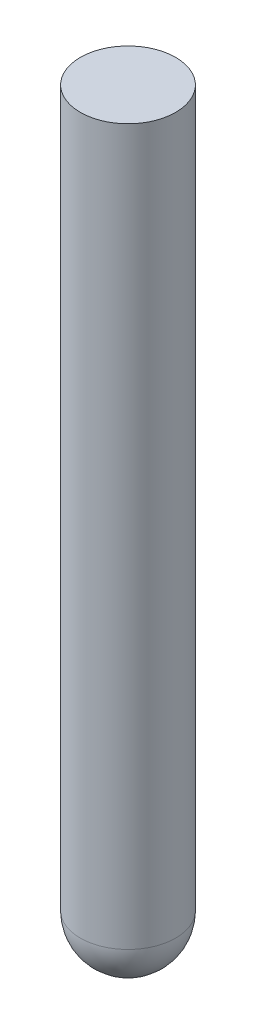
SolidWorks part; units mm, degrees
ref_plane "Front Plane" through (0, 0, 0) normal (0, 0, 1) x (1, 0, 0)
ref_plane "Top Plane" through (0, 0, 0) normal (0, 1, 0) x (1, 0, 0)
ref_plane "Right Plane" through (0, 0, 0) normal (1, 0, 0) x (0, 0, -1)
sketch "Sketch1" plane through (0, 0, 0) normal (0, 1, 0) x (1, 0, 0)
  circle A0 centre (0, 0) radius 3.175
  dimension "D1" = 6.35
extrude "Boss-Extrude1" add sketch "Sketch1" along normal blind 50.8
fillet "Fillet1" radius 3.175 1 edges at (0, 0, 3.175)
